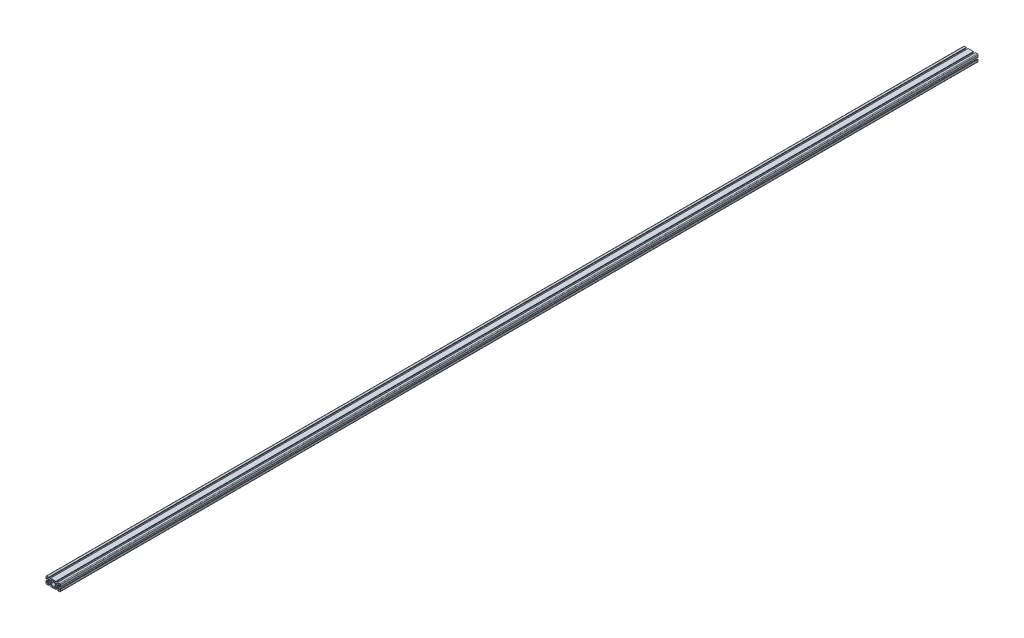
SolidWorks part; units mm, degrees
ref_plane "Front Plane" through (0, 0, 0) normal (0, 0, 1) x (1, 0, 0)
ref_plane "Top Plane" through (0, 0, 0) normal (0, 1, 0) x (1, 0, 0)
ref_plane "Right Plane" through (0, 0, 0) normal (1, 0, 0) x (0, 0, -1)
sketch "Sketch1" plane through (0, 0, 0) normal (0, 0, 1) x (1, 0, 0)
  line L0 (10, 10) -> (10, -10) construction
  line L1 (-20, 0) -> (20, 0) construction
  line L2 (12.5, -10) -> (20, -10)
  line L3 (20, -10) -> (20, -2.5)
  line L4 (12.5, -10) -> (12.5, -8.2134)
  line L5 (12.5, -8.2134) -> (16.95, -8.2134)
  line L6 (16.95, -8.2134) -> (12.3366, -3.6)
  line L7 (10, 0) -> (20, -10) construction
  line L8 (20, -2.5) -> (18.2134, -2.5)
  line L9 (18.2134, -2.5) -> (18.2134, -6.95)
  line L10 (18.2134, -6.95) -> (13.6, -2.3366)
  line L11 (15.9067, -4.6433) -> (14.6433, -5.9067) construction
  line L12 (0, 10) -> (0, -10) construction
  line L13 (0, -10) -> (-20, -10) construction
  line L14 (-10, 10) -> (10, 10) construction
  line L15 (20, 2.5) -> (20, -2.5) construction
  circle A0 centre (10, 0) radius 2.15
  arc A1 (15.5015, -8.2134) -> (15.9257, -7.1891) centre (15.5015, -7.6134) ccw construction
  point P8 (10, -3.6)
  point P16 (15.275, -5.275)
  point P30 (20, 0)
  dimension "Center Hole Diameter" = 4.3
  dimension "D3" = 0.6
  dimension "Rail Width" = 20
  dimension "T-Slot Width" = 5
  dimension "Slot Depth" = 6.4
  dimension "Rail Height" = 40
  dimension "Inner Slot Width" = 13.9
  dimension "Hole Spacing" = 20
sketch "Sketch2" plane through (0, 0, 0) normal (1, 0, 0) x (0, 0, -1)
  line L0 (-1280, -10) -> (1280, -10) construction
  line L1 (-1240, 0) -> (1240, 0) construction
  point P6 (-1240, 0)
  point P8 (1240, 0)
  dimension "Length" = 2560
  dimension "D1" = 40
sketch "Sketch3" plane through (0, 0, 0) normal (0, 0, 1) x (1, 0, 0)
  line L0 (12.5, -10) -> (17.9, -10)
  line L1 (12.5, -10) -> (20, -10) construction
  line L2 (12.5, -10) -> (12.5, -8.2134) construction
  line L3 (12.5, -8.2134) -> (16.95, -8.2134) construction
  line L4 (12.5, -8.2134) -> (12.5, -10)
  line L5 (12.5, -8.2134) -> (16.95, -8.2134)
  line L6 (10, -3.6) -> (12.3366, -3.6)
  line L7 (16.95, -8.2134) -> (12.3366, -3.6) construction
  line L8 (12.3366, -3.6) -> (16.95, -8.2134)
  line L9 (20, -10) -> (20, -2.5) construction
  line L10 (18.2134, -6.95) -> (13.6, -2.3366) construction
  line L11 (18.2134, -2.5) -> (18.2134, -6.95) construction
  line L12 (18.2134, -6.95) -> (18.2134, -2.5)
  line L13 (20, -2.5) -> (18.2134, -2.5) construction
  line L14 (18.2134, -2.5) -> (20, -2.5)
  line L15 (20, -2.5) -> (20, -7.9)
  line L16 (18.2134, -6.95) -> (13.6, -2.3366)
  line L17 (13.6, 0) -> (13.6, -2.3366)
  line L18 (-20, 0) -> (20, 0) construction
  line L19 (10, -3.6) -> (10, -2.15)
  line L20 (10, 10) -> (10, -10) construction
  line L21 (13.6, 0) -> (12.15, 0)
  arc A5 (17.9, -10) -> (20, -7.9) centre (17.9, -7.9) ccw
  circle A10 centre (10, 0) radius 2.15 construction
  arc A11 (10, -2.15) -> (12.15, 0) centre (10, 0) ccw
  dimension "D1" = 2.1
extrude "Boss-Extrude1" add sketch "Sketch3" along normal mid plane 2560
sketch "Sketch4" plane through (0, 0, 0) normal (0, 0, 1) x (1, 0, 0)
  line L0 (10, -3.6) -> (7.6634, -3.6)
  line L4 (7.6634, -3.6) -> (3.05, -8.2134)
  line L5 (3.05, -8.2134) -> (7.5, -8.2134)
  line L6 (7.5, -8.2134) -> (7.5, -10)
  line L18 (7.5, -10) -> (0, -10)
  line L19 (12.5, -10) -> (12.5, -8.2134) construction
  line L20 (12.5, -8.2134) -> (16.95, -8.2134) construction
  line L21 (10, -3.6) -> (12.3366, -3.6) construction
  line L22 (16.95, -8.2134) -> (12.3366, -3.6) construction
  line L23 (0, -8.7366) -> (6.4, -2.3366)
  line L24 (0, 10) -> (0, -10) construction
  line L25 (6.4, -2.3366) -> (6.4, 0)
  line L26 (-20, 0) -> (20, 0) construction
  line L27 (6.4, 0) -> (7.85, 0)
  line L28 (13.6, 0) -> (12.15, 0) construction
  line L29 (0, -8.7366) -> (0, -10)
  line L30 (10, -2.15) -> (10, -3.6)
  circle A4 centre (10, 0) radius 2.15 construction
  arc A5 (7.85, 0) -> (10, -2.15) centre (10, 0) ccw
extrude "Boss-Extrude2" add sketch "Sketch4" along normal mid plane 2560
mirror "Mirror1" about plane through (0, 0, 0) normal (1, 0, 0) of bodies 137 134
mirror "Mirror2" about plane through (0, 0, 0) normal (0, 1, 0) of bodies 135
fillet "Fillet1" radius 0.75 24 edges at (-7.6634, -3.6, 0) (-12.3366, -3.6, 0) (12.3366, -3.6, 0) (7.6634, -3.6, 0) (-3.05, -8.2134, 0) (-18.2134, -6.95, 0) (-16.95, -8.2134, 0) (-13.6, -2.3366, 0) (-18.2134, 6.95, 0) (-16.95, 8.2134, 0) (-12.3366, 3.6, 0) (-7.6634, 3.6, 0) (-3.05, 8.2134, 0) (-13.6, 2.3366, 0) (3.05, 8.2134, 0) (13.6, -2.3366, 0) (13.6, 2.3366, 0) (7.6634, 3.6, 0) (12.3366, 3.6, 0) (16.95, 8.2134, 0) (18.2134, 6.95, 0) (18.2134, -6.95, 0) (16.95, -8.2134, 0) (3.05, -8.2134, 0)
fillet "Fillet2" radius 1.25 6 edges at (0, -8.7366, 0) (-6.4, -2.3366, 0) (-6.4, 2.3366, 0) (6.4, -2.3366, 0) (6.4, 2.3366, 0) (0, 8.7366, 0)
equation "\"D1@Sketch3\" = \"D3@Sketch1\" * 3.5"
equation "\"D1@Boss-Extrude1\" = \"Length@Sketch2\""
equation "\"D1@Boss-Extrude2\" = \"Length@Sketch2\""
equation "\"D1@Sketch2\"=\"Rail Height@Sketch1\""
